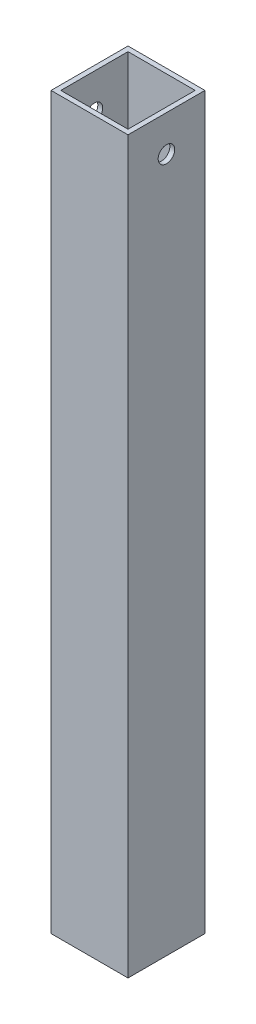
SolidWorks part; units mm, degrees
ref_plane "Front Plane" through (0, 0, 0) normal (0, 0, 1) x (1, 0, 0)
ref_plane "Top Plane" through (0, 0, 0) normal (0, 1, 0) x (1, 0, 0)
ref_plane "Right Plane" through (0, 0, 0) normal (1, 0, 0) x (0, 0, -1)
sketch "Sketch1" plane through (0, 0, 0) normal (0, 1, 0) x (1, 0, 0)
  line L0 (-6.9, -6.9) -> (-6.9, 6.9)
  line L1 (-7.9, -7.9) -> (7.9, -7.9)
  line L2 (-7.9, -7.9) -> (-7.9, 7.9)
  line L3 (-7.9, 7.9) -> (7.9, 7.9)
  line L4 (7.9, -7.9) -> (7.9, 7.9)
  line L5 (-7.9, -7.9) -> (7.9, 7.9) construction
  line L6 (-7.9, 7.9) -> (7.9, -7.9) construction
  line L7 (-6.9, 6.9) -> (6.9, 6.9)
  line L8 (6.9, -6.9) -> (6.9, 6.9)
  line L9 (-6.9, -6.9) -> (6.9, -6.9)
  point P0 (0, 0)
  dimension "D1" = 1
extrude "Boss-Extrude1" add sketch "Sketch1" along normal blind 150
sketch "Sketch2" plane through (-7.9, 0, 0) normal (-1, 0, 0) x (0, 0, 1)
  line L0 (-7.9, 150) -> (7.9, 150) construction
  circle A0 centre (0, 142.6) radius 1.7
  dimension "D1" = 3.4
  dimension "D2" = 7.4
extrude "Cut-Extrude1" cut sketch "Sketch2" against normal through all
